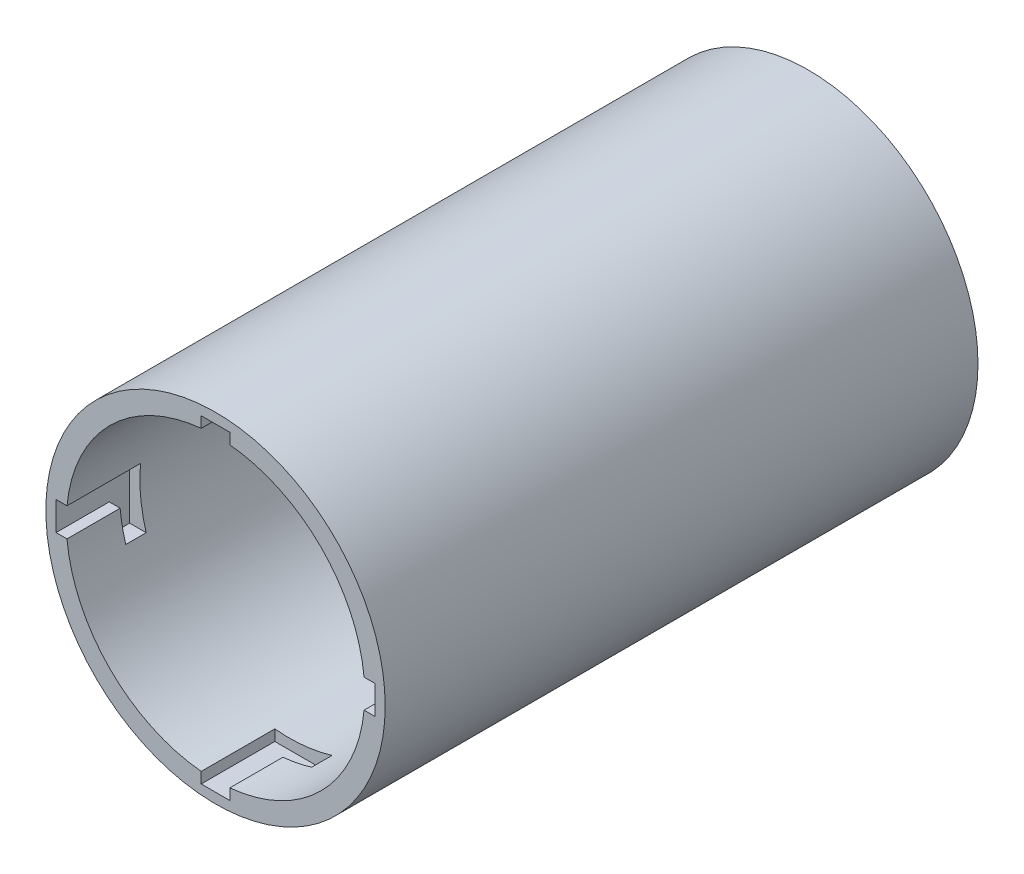
SolidWorks part; units mm, degrees
ref_plane "Front Plane" through (0, 0, 0) normal (0, 0, 1) x (1, 0, 0)
ref_plane "Top Plane" through (0, 0, 0) normal (0, 1, 0) x (1, 0, 0)
ref_plane "Right Plane" through (0, 0, 0) normal (1, 0, 0) x (0, 0, -1)
sketch "Sketch2" plane through (0, 0, 0) normal (0, 0, 1) x (1, 0, 0)
  circle A0 centre (0, 0) radius 36.5
  circle A2 centre (0, 0) radius 41.5
  dimension "D1" = 5
  dimension "D2" = 73
extrude "Boss-Extrude2" add sketch "Sketch2" along normal blind 140
sketch "Sketch13" plane through (0, 0, 0) normal (0, 0, 1) x (1, 0, 0)
  circle A0 centre (0, 0) radius 41.5
  circle A2 centre (0, 0) radius 4.5
  dimension "D1" = 83
  dimension "D2" = 9
extrude "Boss-Extrude3" add sketch "Sketch13" against normal blind 5
sketch "Sketch14" plane through (0, 0, 0) normal (0, 1, 0) x (1, 0, 0)
  line L0 (3.5, -127) -> (10.5, -127)
  line L1 (-36.5, -140) -> (36.5, -140) construction
  line L2 (3.5, -140) -> (3.5, -127)
  line L4 (-3.5, -122) -> (-3.5, -140)
  line L5 (-3.5, -140) -> (3.5, -140)
  line L6 (10.5, -127) -> (10.5, -122)
  line L7 (10.5, -122) -> (-3.5, -122)
extrude "Cut-Extrude1" cut sketch "Sketch14" against normal blind 39
sketch "Sketch16" plane through (0, 0, 0) normal (1, 0, 0) x (0, 0, -1)
  line L1 (-140, 36.5) -> (-140, -36.3318) construction
  line L3 (-140, 3.5486) -> (-127, 3.5486)
  line L4 (-127, 3.5486) -> (-127, 10.5486)
  line L5 (-127, 10.5486) -> (-122, 10.5486)
  line L6 (-122, 10.5486) -> (-122, -3.4514)
  line L7 (-122, -3.4514) -> (-140, -3.4514)
  line L8 (-140, 41.5) -> (-140, -41.5) construction
  line L9 (-140, -3.4514) -> (-140, 3.5486)
extrude "Cut-Extrude2" cut sketch "Sketch16" along normal blind 39
sketch "Sketch19" plane through (0, 0, 0) normal (0, 1, 0) x (1, 0, 0)
  line L3 (3.5, -140) -> (36.3365, -140) construction
  line L4 (3.5, -140) -> (3.5, -122)
  line L5 (3.5, -122) -> (-10.5, -122)
  line L6 (-10.5, -122) -> (-10.5, -127)
  line L7 (-10.5, -127) -> (-3.5, -127)
  line L8 (-3.5, -127) -> (-3.5, -140)
  line L9 (-3.5, -140) -> (3.5, -140)
extrude "Cut-Extrude3" cut sketch "Sketch19" along normal blind 39
sketch "Sketch20" plane through (0, 0, 0) normal (1, 0, 0) x (0, 0, -1)
  line L1 (-140, 41.5) -> (-140, -41.5) construction
  line L2 (-127, -3.5) -> (-140, -3.5)
  line L3 (-140, 3.5) -> (-122, 3.5)
  line L4 (-122, 3.5) -> (-122, -10.5)
  line L5 (-122, -10.5) -> (-127, -10.5)
  line L6 (-127, -10.5) -> (-127, -3.5)
  line L9 (-140, -3.5) -> (-140, 3.5)
extrude "Cut-Extrude4" cut sketch "Sketch20" against normal blind 39
